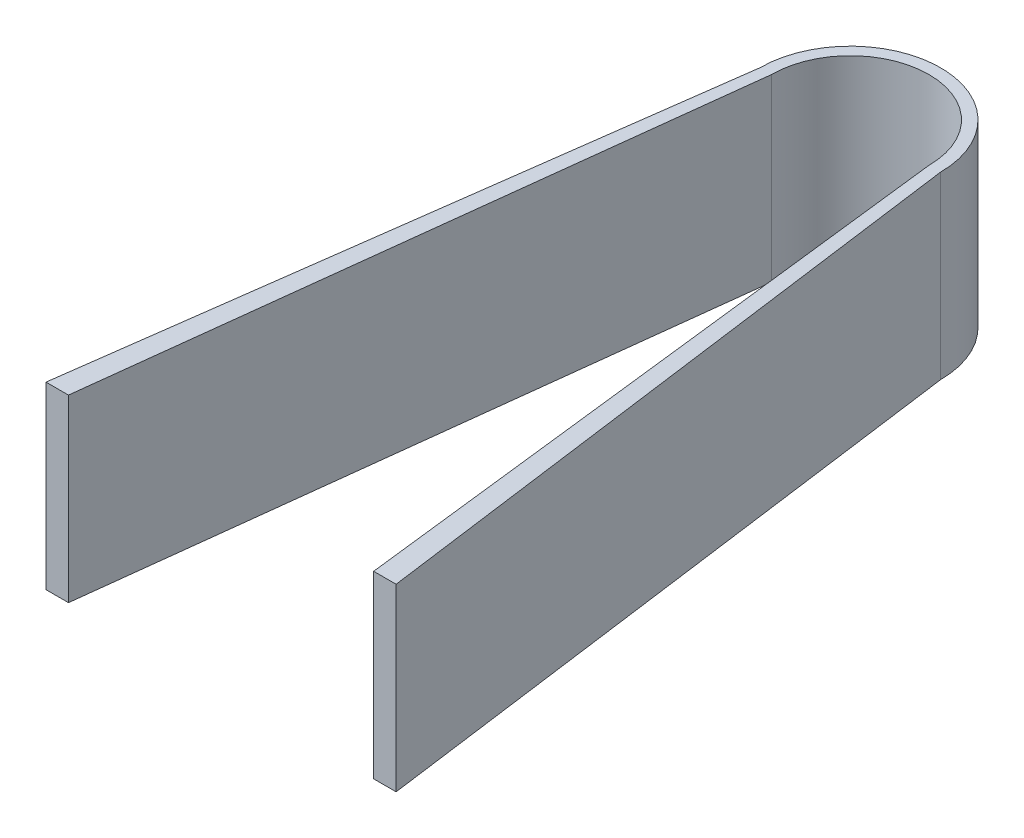
SolidWorks part; units mm, degrees
ref_plane "Front Plane" through (0, 0, 0) normal (0, 0, 1) x (1, 0, 0)
ref_plane "Top Plane" through (0, 0, 0) normal (0, 1, 0) x (1, 0, 0)
ref_plane "Right Plane" through (0, 0, 0) normal (1, 0, 0) x (0, 0, -1)
sketch "Sketch1" plane through (0, 0, 0) normal (0, 1, 0) x (1, 0, 0)
  line L0 (-11.1125, 0) -> (-21.558, -88.8989)
  line L1 (0, 0) -> (0, -88.8989) construction
  line L2 (21.558, -88.8989) -> (24.733, -88.8989) construction
  line L3 (24.733, -88.8989) -> (21.558, -88.8989) construction
  line L4 (11.1125, 0) -> (21.558, -88.8989)
  line L5 (-12.7635, 0) -> (-24.733, -88.8989)
  line L6 (12.7635, 0) -> (24.733, -88.8989)
  line L7 (-24.733, -88.8989) -> (-21.558, -88.8989)
  line L8 (21.558, -88.8989) -> (24.733, -88.8989)
  line L9 (-21.558, -88.8989) -> (-24.733, -88.8989) construction
  arc A0 (11.1125, 0) -> (-11.1125, 0) centre (0, 0) ccw
  arc A1 (12.7635, 0) -> (-12.7635, 0) centre (0, 0) ccw
  dimension "D1" = 22.225
  dimension "D2" = 25.527
  dimension "D3" = 3.175
extrude "Boss-Extrude1" add sketch "Sketch1" along normal blind 25.4
